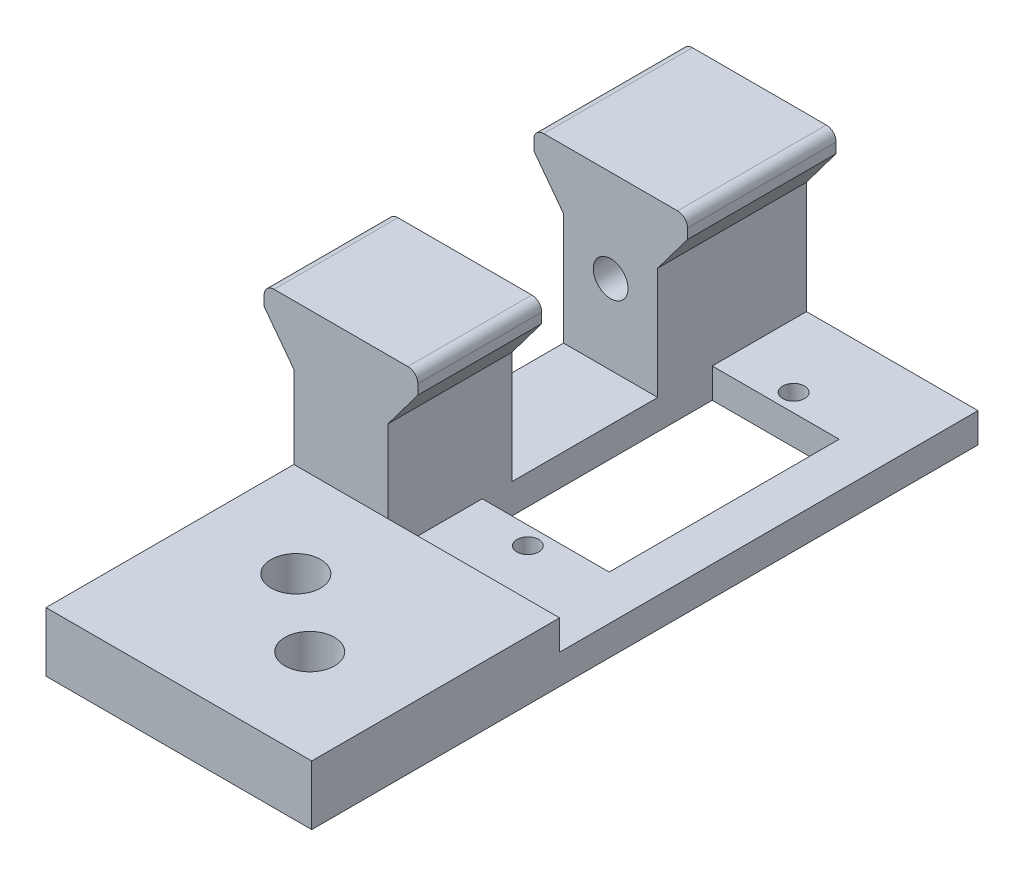
SolidWorks part; units mm, degrees
ref_plane "前视基准面" through (0, 0, 0) normal (0, 0, 1) x (1, 0, 0)
ref_plane "上视基准面" through (0, 0, 0) normal (0, 1, 0) x (1, 0, 0)
ref_plane "右视基准面" through (0, 0, 0) normal (1, 0, 0) x (0, 0, -1)
sketch "草图5" plane through (0, 0, 0) normal (0, 1, 0) x (1, 0, 0)
  line L0 (5.25, -27.2) -> (5.25, -25.2599) construction
  line L1 (6.55, -25.2599) -> (6.55, -27.2) construction
  line L2 (6.55, -27.2) -> (11.8, -27.2) construction
  line L3 (11.8, -27.2) -> (11.8, -22.2) construction
  line L4 (11.8, -22.2) -> (0, -22.2) construction
  line L5 (0, -22.2) -> (0, -27.2) construction
  line L6 (0, -27.2) -> (5.25, -27.2) construction
  line L7 (5.25, 3.0599) -> (5.25, 5) construction
  line L8 (5.25, 5) -> (0, 5) construction
  line L9 (0, 5) -> (0, 0) construction
  line L10 (0, 0) -> (11.8, 0) construction
  line L11 (11.8, 0) -> (11.8, 5) construction
  line L12 (11.8, 5) -> (6.55, 5) construction
  line L13 (6.55, 5) -> (6.55, 3.0599) construction
  line L14 (5.25, -27.2) -> (5.25, -25.2599) construction
  line L15 (6.55, -25.2599) -> (6.55, -27.2) construction
  line L16 (6.55, -27.2) -> (11.8, -27.2) construction
  line L17 (11.8, -27.2) -> (11.8, -22.2) construction
  line L18 (11.8, -22.2) -> (0, -22.2) construction
  line L19 (0, -22.2) -> (0, -27.2) construction
  line L20 (0, -27.2) -> (5.25, -27.2) construction
  line L21 (5.25, 3.0599) -> (5.25, 5) construction
  line L22 (5.25, 5) -> (0, 5) construction
  line L23 (0, 5) -> (0, 0) construction
  line L24 (0, 0) -> (11.8, 0) construction
  line L25 (11.8, 0) -> (11.8, 5) construction
  line L26 (11.8, 5) -> (6.55, 5) construction
  line L27 (6.55, 5) -> (6.55, 3.0599) construction
  line L30 (-10, 10) -> (16.8, 10)
  line L31 (-10, 10) -> (-10, -32.2)
  line L32 (-10, -32.2) -> (16.8, -32.2)
  line L33 (16.8, 10) -> (16.8, -32.2)
  line L35 (11.8, -16.3) -> (11.8, 0) construction
  line L36 (-0.5, -22.7) -> (12.3, -22.7)
  line L37 (-0.5, -22.7) -> (-0.5, 0.5)
  line L38 (-0.5, 0.5) -> (12.3, 0.5)
  line L39 (12.3, -22.7) -> (12.3, 0.5)
  line L40 (0, -16.3) -> (0, 0) construction
  arc A0 (6.55, -25.2599) -> (5.25, -25.2599) centre (5.9, -24.5) ccw construction
  arc A1 (5.25, 3.0599) -> (6.55, 3.0599) centre (5.9, 2.3) ccw construction
  arc A2 (6.55, -25.2599) -> (5.25, -25.2599) centre (5.9, -24.5) ccw construction
  arc A3 (5.25, 3.0599) -> (6.55, 3.0599) centre (5.9, 2.3) ccw construction
  circle A4 centre (5.9, 2.3) radius 1.1
  circle A5 centre (5.9, -24.5) radius 1.1
  dimension "D5" = 2.2
  dimension "D6" = 2.2
  dimension "D1" = 5
  dimension "D2" = 10
  dimension "D3" = 5
  dimension "D4" = 5
  dimension "D7" = 0.5
  dimension "D8" = 0.5
  dimension "D9" = 0.5
  dimension "D10" = 0.5
extrude "凸台-拉伸1" add sketch "草图5" along normal blind 3
sketch "草图7" plane through (0, 3, 0) normal (0, 1, 0) x (1, 0, 0)
  line L0 (-0.5, 0.5) -> (-0.5, -22.7) construction
  line L1 (-10, 10) -> (-0.5, 10)
  line L10 (-10, 10) -> (-10, -5)
  line L11 (-10, -5) -> (-0.5, -5)
  line L12 (-0.5, 10) -> (-0.5, -5)
  line L14 (-10, -32.2) -> (-0.5, -32.2)
  line L15 (-10, -32.2) -> (-10, -19.7)
  line L16 (-10, -19.7) -> (-0.5, -19.7)
  line L17 (-0.5, -32.2) -> (-0.5, -19.7)
  dimension "D1" = 15
  dimension "D2" = 12.5
extrude "凸台-拉伸2" add sketch "草图7" along normal blind 17.3
sketch "草图10" plane through (0, 0, 5) normal (0, 0, 1) x (1, 0, 0)
  line L0 (-5.25, 3) -> (-5.25, 11) construction
  line L1 (-10, 3) -> (-0.5, 3) construction
  circle A0 centre (-5.25, 11) radius 1.75
  dimension "D1" = 3.5
  dimension "D2" = 8
extrude "切除-拉伸2" cut sketch "草图10" against normal blind 10
sketch "草图13" plane through (0, 0, 32.2) normal (0, 0, 1) x (1, 0, 0)
  line L0 (-5.25, 20.3) -> (-5.25, 14.6293) construction
  line L1 (-0.5, 20.3) -> (2.5, 20.3)
  line L2 (-0.5, 20.3) -> (-0.5, 15.5539)
  line L4 (2.5, 20.3) -> (2.5, 18.3)
  line L6 (2.5, 18.3) -> (-0.5, 14.3)
  line L8 (-0.5, 15.5539) -> (-0.5, 14.3)
  line L9 (-10, 15.5539) -> (-10, 14.3)
  line L10 (-13, 18.3) -> (-10, 14.3)
  line L11 (-13, 20.3) -> (-13, 18.3)
  line L12 (-10, 20.3) -> (-10, 15.5539)
  line L13 (-10, 20.3) -> (-13, 20.3)
  line L14 (-10, 20.3) -> (-0.5, 20.3) construction
  line L15 (-0.5, 20.3) -> (-0.5, 3) construction
  point P12 (-5.25, 20.3)
  dimension "D1" = 3
  dimension "D2" = 2
  dimension "D3" = 6
extrude "凸台-拉伸3" add sketch "草图13" against normal up to surface (42.2 mm away)
sketch "草图16" plane through (0, 20.3, 0) normal (0, 1, 0) x (1, 0, 0)
  line L0 (2.5, 10) -> (2.5, -32.2) construction
  line L1 (2.5, -5) -> (-13, -5)
  line L2 (2.5, -5) -> (2.5, -19.7)
  line L3 (2.5, -19.7) -> (-13, -19.7)
  line L4 (-13, -5) -> (-13, -19.7)
  line L5 (-13, 10) -> (-13, -32.2) construction
  line L6 (-0.5, -19.7) -> (-10, -19.7) construction
  line L7 (-10, -5) -> (-0.5, -5) construction
extrude "切除-拉伸3" cut sketch "草图16" against normal up to surface (17.3 mm away) up to face at (-5.25, 3, 12.35)
fillet "圆角1" radius 1 2 edges at (-13, 20.3, 25.95) (2.5, 20.3, 25.95)
sketch "草图20" plane through (0, 0, 32.2) normal (0, 0, 1) x (1, 0, 0)
  line L0 (16.8, 3) -> (16.8, 0) construction
  line L1 (-10, 0) -> (16.8, 0)
  line L2 (-10, 0) -> (-10, 6)
  line L3 (-10, 6) -> (16.8, 6)
  line L4 (16.8, 0) -> (16.8, 6)
  dimension "D1" = 6
extrude "凸台-拉伸5" add sketch "草图20" along normal blind 25
sketch "草图21" plane through (0, 6, 0) normal (0, 1, 0) x (1, 0, 0)
  line L0 (-10, -57.2) -> (16.8, -32.2) construction
  line L2 (-0.35, -41.65) -> (7.15, -41.65) construction
  line L3 (-0.35, -41.65) -> (-0.35, -47.75) construction
  line L4 (-0.35, -47.75) -> (7.15, -47.75) construction
  line L5 (7.15, -41.65) -> (7.15, -47.75) construction
  line L6 (-0.35, -41.65) -> (7.15, -47.75) construction
  line L7 (-0.35, -47.75) -> (7.15, -41.65) construction
  circle A0 centre (7.15, -47.75) radius 2.5
  circle A1 centre (-0.35, -41.65) radius 2.5
  point P4 (3.4, -44.7)
  dimension "D3" = 5
  dimension "D4" = 5
  dimension "D1" = 7.5
  dimension "D2" = 6.1
extrude "切除-拉伸6" cut sketch "草图21" against normal blind 4
sketch "草图22" plane through (0, 2, 0) normal (0, 1, 0) x (1, 0, 0)
  circle A0 centre (-0.35, -41.65) radius 1.1
  circle A1 centre (7.15, -47.75) radius 2.5
  circle A2 centre (7.15, -47.75) radius 2.5 construction
  circle A3 centre (-0.35, -41.65) radius 2.5
  circle A4 centre (-0.35, -41.65) radius 2.5 construction
  circle A5 centre (7.15, -47.75) radius 1.1
  dimension "D3" = 2.2
  dimension "D4" = 2.2
  dimension "D1" = 0
  dimension "D2" = 0
extrude "切除-拉伸7" cut sketch "草图22" against normal through all
equation "\"m\"= 2"
